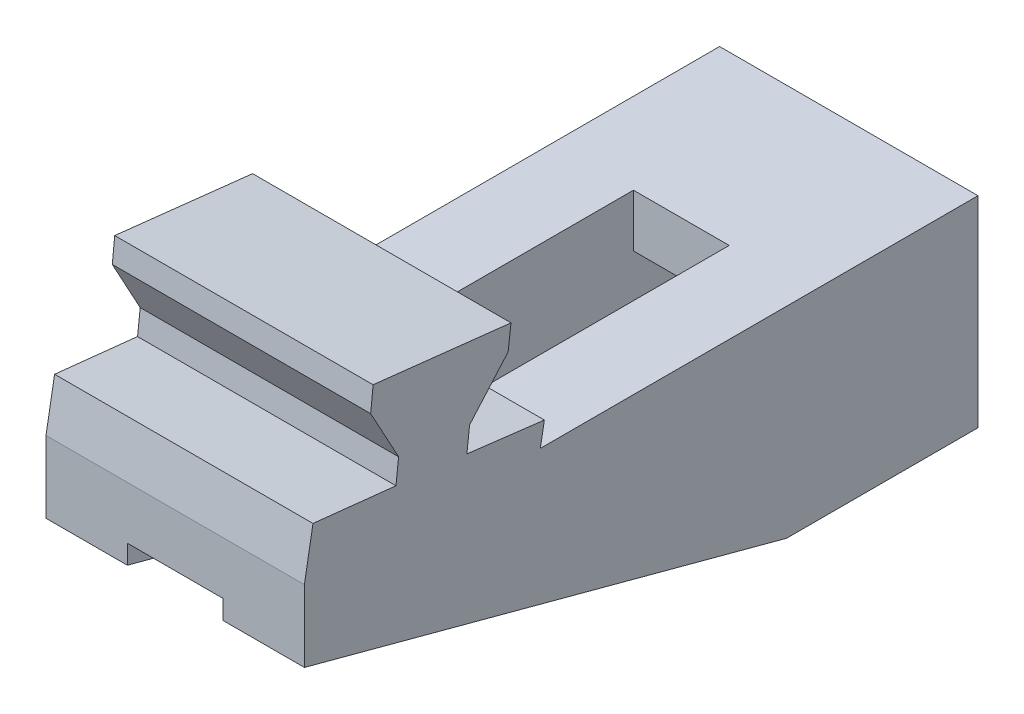
SolidWorks part; units mm, degrees
ref_plane "Front" through (0, 0, 0) normal (0, 0, 1) x (1, 0, 0)
ref_plane "Top" through (0, 0, 0) normal (0, 1, 0) x (1, 0, 0)
ref_plane "Right" through (0, 0, 0) normal (1, 0, 0) x (0, 0, -1)
sketch "Sketch1" plane through (0, 0, 0) normal (0, 0, 1) x (1, 0, 0)
  line L1 (0, 0) -> (54, 0)
  line L2 (0, 0) -> (0, 42)
  line L3 (0, 42) -> (54, 42)
  line L4 (54, 0) -> (54, 42)
  dimension "D1" = 54
  dimension "D2" = 42
extrude "Boss-Extrude1" add sketch "Sketch1" along normal blind 40
sketch "Sketch5" plane through (0, 0, 0) normal (-1, 0, 0) x (0, 0, 1)
  line L1 (140.7654, 42) -> (40, 42)
  line L2 (40, 42) -> (40, 0)
  line L3 (40, 0) -> (140.7654, 27)
  line L4 (140.7654, 27) -> (140.7654, 42)
  dimension "D1" = 75
  dimension "D2" = 15
extrude "Boss-Extrude2" add sketch "Sketch5" against normal up to surface (54 mm away) up to face at (54, 21, 20)
ref_plane "Plane1" through (27, 0, 0) normal (1, 0, 0) x (0, 0, -1)
sketch "Sketch12" plane through (0, 42, 0) normal (0, 1, 0) x (1, 0, 0)
  line L0 (54, 0) -> (0, 0) construction
  line L1 (17, -35) -> (37, -35)
  line L2 (17, -35) -> (17, -100.7654)
  line L3 (17, -100.7654) -> (37, -100.7654)
  line L4 (37, -35) -> (37, -100.7654)
  line L7 (54, -140.7654) -> (0, -140.7654) construction
  line L8 (0, -140.7654) -> (0, 0) construction
  dimension "D1" = 35
  dimension "D2" = 20
  dimension "D3" = 17
  dimension "D4" = 40
extrude "Cut-Extrude5" cut sketch "Sketch12" against normal through all
sketch "Sketch13" plane through (0, 0, 0) normal (0, 0, -1) x (-1, 0, 0)
  line L0 (-37, 31) -> (-37, 11)
  line L5 (-37, 11) -> (-17, 11)
  line L7 (-54, 0) -> (-54, 42) construction
  line L8 (-54, 42) -> (0, 42) construction
  line L12 (-37, 31) -> (-17, 31)
  line L13 (-17, 31) -> (-17, 11)
  dimension "D1" = 20
  dimension "D2" = 20
  dimension "D3" = 17
  dimension "D4" = 11
extrude "Cut-Extrude6" cut sketch "Sketch13" against normal through all
sketch "Sketch14" plane through (0, 0, 0) normal (0, 0, -1) x (-1, 0, 0)
  line L0 (-54, 42) -> (0, 42) construction
  line L1 (-49.2, 37.2) -> (-41.3, 37.2)
  line L2 (-49.2, 37.2) -> (-49.2, 29.3)
  line L3 (-49.2, 29.3) -> (-41.3, 29.3)
  line L4 (-41.3, 37.2) -> (-41.3, 29.3)
  line L5 (-54, 0) -> (-54, 42) construction
  line L6 (-27, 42) -> (-27, 0)
  line L7 (0, 0) -> (-54, 0) construction
  line L8 (-4.8, 29.3) -> (-12.7, 29.3)
  line L9 (-12.7, 37.2) -> (-12.7, 29.3)
  line L10 (-4.8, 37.2) -> (-12.7, 37.2)
  line L11 (-4.8, 37.2) -> (-4.8, 29.3)
  line L12 (-54, 21) -> (0, 21)
  line L13 (0, 42) -> (0, 0) construction
  line L14 (-4.8, 4.8) -> (-4.8, 12.7)
  line L15 (-4.8, 4.8) -> (-12.7, 4.8)
  line L16 (-12.7, 4.8) -> (-12.7, 12.7)
  line L17 (-4.8, 12.7) -> (-12.7, 12.7)
  line L18 (-49.2, 12.7) -> (-41.3, 12.7)
  line L19 (-41.3, 4.8) -> (-41.3, 12.7)
  line L20 (-49.2, 4.8) -> (-41.3, 4.8)
  line L21 (-49.2, 4.8) -> (-49.2, 12.7)
  dimension "D1" = 7.9
  dimension "D2" = 7.9
  dimension "D3" = 4.8
  dimension "D4" = 4.8
extrude "Cut-Extrude7" cut sketch "Sketch14" against normal blind 20.2 contours L4 L1 L2 L3 | L21 L20 L19 L18 | L11 L10 L9 L8 | L14 L17 L16 L15
ref_plane "Plane2" through (0, 42, 0) normal (0, 0, -1) x (-1, 0, 0)
sketch "Sketch16" plane through (54, 0, 0) normal (1, 0, 0) x (0, 0, -1)
  line L0 (-140.7654, 42) -> (-135.4756, 72)
  line L6 (-140.7654, 42) -> (0, 42) construction
  line L7 (-91.4535, 42) -> (-140.7654, 42)
  line L8 (-91.4535, 42) -> (-87.1123, 66.6202)
  line L9 (-87.1123, 66.6202) -> (-135.4756, 72)
  dimension "D1" = 80
  dimension "D2" = 30
  dimension "D3" = 100
  dimension "D4" = 25
extrude "Boss-Extrude3" add sketch "Sketch16" against normal blind 54
ref_plane "Plane3" through (54, 66.6202, 87.1123) normal (0, 0.9848, -0.1736) x (1, 0, 0)
sketch "Sketch18" plane through (54, 0, 0) normal (1, 0, 0) x (0, 0, -1)
  line L1 (-87.1123, 66.6202) -> (-135.4756, 72) construction
  line L4 (-126.4067, 70.9912) -> (-135.4756, 72)
  line L7 (-126.4067, 70.9912) -> (-126.9167, 66.0173)
  line L8 (-97.5845, 67.7851) -> (-98.2013, 62.8233)
  line L9 (-121.0801, 55.2927) -> (-126.9167, 66.0173)
  line L10 (-106.2517, 53.6432) -> (-98.2013, 62.8233)
  line L12 (-121.0801, 55.2927) -> (-121.6329, 50.3233)
  line L13 (-106.8045, 48.6738) -> (-106.2517, 53.6432)
  line L14 (-135.4756, 72) -> (-138.972, 52.1705)
  line L15 (-135.4756, 72) -> (-140.7654, 42) construction
  line L16 (-138.972, 52.1705) -> (-121.6329, 50.3233)
  line L17 (-97.5845, 67.7851) -> (-87.1123, 66.6202)
  line L18 (-87.1123, 66.6202) -> (-90.6225, 46.7128)
  line L19 (-91.4535, 42) -> (-87.1123, 66.6202) construction
  line L20 (-90.6225, 46.7128) -> (-106.8045, 48.6738)
  dimension "D1" = 5
  dimension "D2" = 5
  dimension "D3" = 5
  dimension "D4" = 5
  dimension "D5" = 12.21
  dimension "D6" = 12.21
  dimension "D7" = 29
extrude "Cut-Extrude8" cut sketch "Sketch18" against normal blind 54
